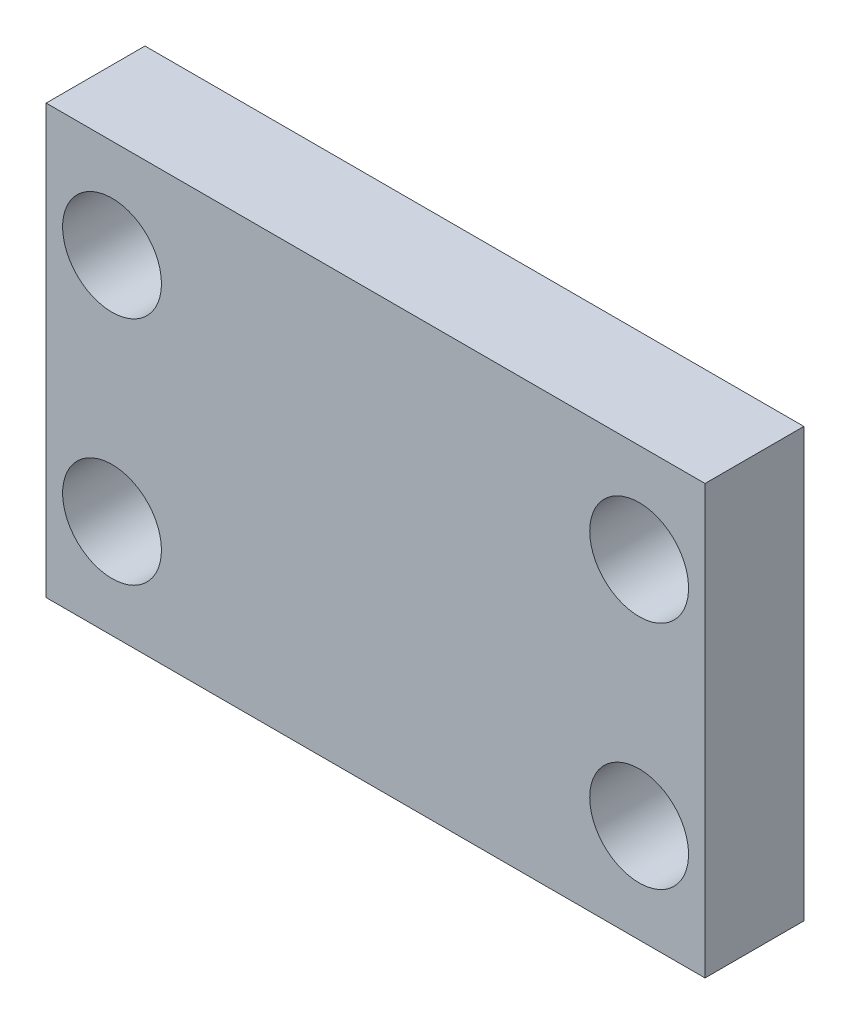
SolidWorks part; units mm, degrees
material "1023 Arkusz stali węglowej (SS)"
ref_plane "Płaszczyzna przednia" through (0, 0, 0) normal (0, 0, 1) x (1, 0, 0)
ref_plane "Płaszczyzna górna" through (0, 0, 0) normal (0, 1, 0) x (1, 0, 0)
ref_plane "Płaszczyzna prawa" through (0, 0, 0) normal (1, 0, 0) x (0, 0, -1)
sketch "Szkic1" plane through (0, 0, 0) normal (0, 0, 1) x (1, 0, 0)
  line L0 (0, -8.9619) -> (0, 10.7418) construction
  line L1 (-10, -6.5) -> (10, -6.5)
  line L2 (-10, -6.5) -> (-10, 6.5)
  line L3 (-10, 6.5) -> (10, 6.5)
  line L4 (10, -6.5) -> (10, 6.5)
  line L5 (-10, -6.5) -> (10, 6.5) construction
  line L6 (-10, 6.5) -> (10, -6.5) construction
  circle A0 centre (-8, 3.5) radius 1.5
  circle A1 centre (-8, -3.5) radius 1.5
  circle A2 centre (8, 3.5) radius 1.5
  circle A3 centre (8, -3.5) radius 1.5
  point P0 (0, 0)
  dimension "D4" = 3
  dimension "D1" = 20
  dimension "D2" = 13
  dimension "D3" = 3
  dimension "D5" = 3
  dimension "D6" = 8
extrude "Dodanie-wyciągnięcie1" add sketch "Szkic1" along normal blind 3
